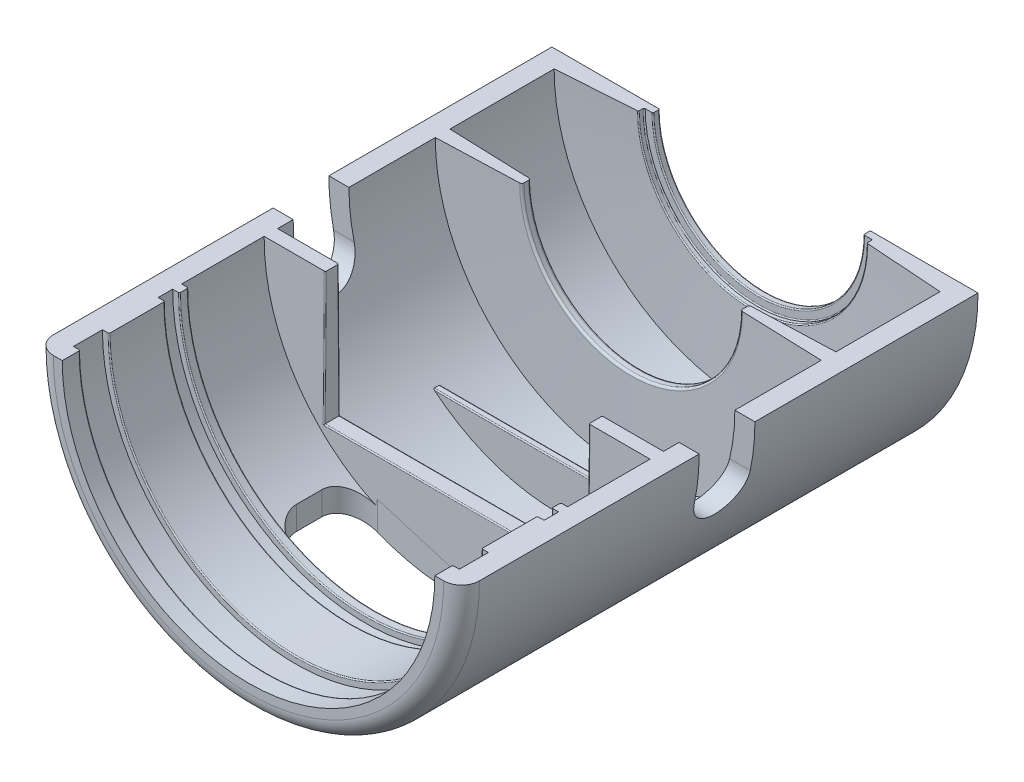
SolidWorks part; units mm, degrees
material "PC High Viscosity"
ref_plane "Front Plane" through (0, 0, 0) normal (0, 0, 1) x (1, 0, 0)
ref_plane "Top Plane" through (0, 0, 0) normal (0, 1, 0) x (1, 0, 0)
ref_plane "Right Plane" through (0, 0, 0) normal (1, 0, 0) x (0, 0, -1)
sketch "Sketch2" plane through (0, 0, 0) normal (0, 0, 1) x (1, 0, 0)
  line L1 (-15, 15) -> (15, 15)
  line L2 (-15, 15) -> (-15, -15)
  line L3 (-15, -15) -> (15, -15)
  line L4 (15, 15) -> (15, -15)
  line L5 (-15, 15) -> (15, -15) construction
  line L6 (-15, -15) -> (15, 15) construction
  circle A0 centre (0, 0) radius 21.971
  circle A1 centre (0, 0) radius 24.257
  point P0 (0, 0)
  dimension "D2" = 2.286
  dimension "D3" = 43.942
  dimension "D1" = 30
sketch "Sketch3" plane through (0, 0, 0) normal (0, 0, 1) x (1, 0, 0)
  line L0 (-24.257, 0) -> (-21.971, 0)
  line L1 (21.971, 0) -> (24.257, 0)
  circle A0 centre (0, 0) radius 24.257 construction
  circle A1 centre (0, 0) radius 21.971 construction
  arc A2 (-21.971, 0) -> (21.971, 0) centre (0, 0) ccw
  arc A3 (-24.257, 0) -> (24.257, 0) centre (0, 0) ccw
extrude "Boss-Extrude1" add sketch "Sketch3" along normal blind 38.1
ref_axis "Axis1" through (0, 0, 38.1) along (0, 0, -1)
ref_plane "Plane1" through (0, 0, 0) normal (0, -1, 0) x (-1, 0, 0)
sketch "Sketch8" plane through (0, 0, 0) normal (0, -1, 0) x (-1, 0, 0)
  line L0 (21.971, 0) -> (21.971, -2.032)
  line L1 (21.971, -38.1) -> (21.971, 0) construction
  line L2 (21.971, -2.032) -> (13.1229, -1.4133)
  line L3 (13.0048, -1.2866) -> (13.0048, -0.889)
  line L4 (12.8778, -0.762) -> (12.1158, -0.762)
  line L5 (11.9888, -0.635) -> (11.9888, -0.127)
  line L6 (21.971, 0) -> (-21.971, 0) construction
  line L7 (12.1158, 0) -> (21.971, 0)
  line L8 (0, -38.1) -> (0, 0) construction
  arc A0 (11.9888, -0.127) -> (12.1158, 0) centre (12.1158, -0.127) cw
  arc A1 (12.1158, -0.762) -> (11.9888, -0.635) centre (12.1158, -0.635) cw
  arc A2 (13.0048, -0.889) -> (12.8778, -0.762) centre (12.8778, -0.889) ccw
  arc A3 (13.1229, -1.4133) -> (13.0048, -1.2866) centre (13.1318, -1.2866) cw
  point P15 (11.9888, 0)
  point P18 (11.9888, -0.762)
  point P21 (13.0048, -0.762)
  dimension "D6" = 0.127
  dimension "D1" = 2.032
  dimension "D2" = 0.762
  dimension "D3" = 1.016
  dimension "D4" = 11.9888
  dimension "D5" = 86
revolve "Revolve1" add sketch "Sketch8" angle 180 about axis through (0, 0, 38.1) along (0, 0, -1)
sketch "Sketch9" plane through (0, 0, 0) normal (0, -1, 0) x (-1, 0, 0)
  line L0 (21.971, -14.732) -> (12.446, -14.732) construction
  line L1 (21.971, -38.1) -> (21.971, -2.032) construction
  line L2 (12.446, -14.9862) -> (12.446, -14.4778)
  line L3 (12.6911, -14.224) -> (21.971, -13.8999)
  line L4 (12.6911, -15.24) -> (21.971, -15.5641)
  line L5 (21.971, -15.5641) -> (21.971, -13.8999)
  line L6 (12.1158, -0.762) -> (12.8778, -0.762) construction
  line L7 (0, -38.1) -> (0, 0) construction
  arc A0 (12.446, -14.4778) -> (12.6911, -14.224) centre (12.7, -14.4778) cw
  arc A1 (12.446, -14.9862) -> (12.6911, -15.24) centre (12.7, -14.9862) ccw
  dimension "D1" = 0.254
  dimension "D2" = 1.016
  dimension "D3" = 4
  dimension "D4" = 13.97
  dimension "D5" = 12.446
revolve "Revolve2" add sketch "Sketch9" angle 180 about axis through (0, 0, 38.1) along (0, 0, -1)
ref_plane "Plane2" through (0, -17.5768, 0) normal (0, -1, 0) x (-1, 0, 0)
sketch "Sketch11" plane through (0, -17.5768, 0) normal (0, -1, 0) x (-1, 0, 0)
  line L0 (0, -36.9414) -> (0, -6.0033) construction
  line L1 (0, -38.1) -> (0, 0) construction
  line L2 (-13.97, -22.098) -> (13.97, -22.098)
  line L3 (13.97, -22.098) -> (13.97, -23.622)
  line L4 (13.97, -23.622) -> (-13.97, -23.622)
  line L5 (-13.97, -22.098) -> (-13.97, -23.622)
  line L6 (13.97, -22.86) -> (-13.97, -22.86) construction
  line L9 (-24.257, 0) -> (-12.1158, 0) construction
  point P10 (0, -23.622)
  point P11 (0, -22.098)
  dimension "D1" = 1.524
  dimension "D2" = 27.94
  dimension "D3" = 22.86
extrude "Boss-Extrude6" add sketch "Sketch11" along normal up to body
ref_plane "Plane3" through (0, -16.8148, 0) normal (0, 1, 0) x (1, 0, 0)
sketch "Sketch12" plane through (0, -16.8148, 0) normal (0, 1, 0) x (1, 0, 0)
  line L0 (14.605, -23.622) -> (-14.605, -23.622)
  line L2 (-13.1826, -23.622) -> (13.1826, -23.622) construction
  line L3 (-14.605, -23.622) -> (-14.605, -22.86)
  line L4 (-14.605, -22.86) -> (14.605, -22.86)
  line L5 (0, -38.1) -> (0, 0) construction
  line L6 (0, -22.86) -> (0, -27.3543) construction
  line L7 (14.605, -23.622) -> (14.605, -22.86)
  point P12 (0, -23.622)
  dimension "D1" = 0.762
  dimension "D2" = 29.21
extrude "Boss-Extrude7" add sketch "Sketch12" against normal up to surface (0.762 mm away) up to face at (0, -17.5768, 22.86)
ref_plane "Plane4" through (0, 0, 0) normal (1, 0, 0) x (0, 0, -1)
sketch "Sketch13" plane through (0, 0, 0) normal (1, 0, 0) x (0, 0, -1)
  line L0 (-22.86, -17.5768) -> (-22.86, 0) construction
  line L2 (-38.1, 0) -> (0, 0) construction
  line L3 (-25.4, 0) -> (-25.4, -5.08)
  line L4 (-31.75, 0) -> (-31.75, -5.08)
  line L5 (-31.75, -5.08) -> (-25.4, -5.08) construction
  line L6 (-38.1, 0) -> (0, 0) construction
  arc A0 (-31.75, -5.08) -> (-25.4, -5.08) centre (-28.575, -5.08) ccw
  point P12 (-28.575, -8.255)
  dimension "D2" = 3.175
  dimension "D1" = 6.35
  dimension "D3" = 2.54
  dimension "D4" = 8.255
extrude "Cut-Extrude1" cut sketch "Sketch13" against normal through all and the other way through all
sketch "Sketch15" plane through (0, 0, 0) normal (0, -1, 0) x (-1, 0, 0)
  line L0 (21.971, -44.45) -> (21.209, -44.45)
  line L1 (21.971, -38.1) -> (21.971, -31.75) construction
  line L2 (21.209, -44.45) -> (21.209, -45.466)
  line L3 (21.209, -45.466) -> (21.971, -45.466)
  line L4 (21.971, -45.466) -> (21.971, -47.117)
  line L5 (21.971, -47.117) -> (21.209, -47.117)
  line L6 (21.209, -47.117) -> (21.209, -53.467)
  line L7 (21.209, -53.467) -> (21.971, -53.467)
  line L8 (21.971, -53.467) -> (21.971, -56.769)
  line L9 (21.971, -56.769) -> (21.209, -56.769)
  line L10 (21.209, -56.769) -> (21.209, -58.801)
  line L11 (21.209, -58.801) -> (24.257, -58.801)
  line L12 (24.257, -58.801) -> (24.257, -52.4274)
  line L13 (24.257, -38.1) -> (24.257, -31.75) construction
  line L14 (24.257, -52.4274) -> (24.257, -44.45)
  line L15 (24.257, -44.45) -> (21.971, -44.45)
  line L16 (14.1417, -22.86) -> (13.1826, -22.86) construction
  line L17 (0, -25.7525) -> (0, -35.3346) construction
  line L18 (0, -38.1) -> (0, 0) construction
  dimension "D1" = 22.606
  dimension "D2" = 21.971
  dimension "D3" = 1.651
  dimension "D4" = 3.302
  dimension "D5" = 6.35
  dimension "D6" = 2.032
  dimension "D7" = 21.209
  dimension "D8" = 0.762
  dimension "D9" = 1.016
revolve "Revolve3" add sketch "Sketch15" angle 180 about axis through (0, 0, 38.1) along (0, 0, -1)
sketch "Sketch16" plane through (0, 0, 38.1) normal (0, 0, 1) x (1, 0, 0)
  line L2 (24.257, 0) -> (21.971, 0)
  line L3 (-21.971, 0) -> (-24.257, 0)
  line L4 (24.257, 0) -> (21.971, 0)
  line L5 (-21.971, 0) -> (-24.257, 0)
  arc A2 (-24.257, 0) -> (24.257, 0) centre (0, 0) ccw
  arc A3 (-21.971, 0) -> (21.971, 0) centre (0, 0) ccw
  arc A4 (-24.257, 0) -> (24.257, 0) centre (0, 0) ccw
  arc A5 (-21.971, 0) -> (21.971, 0) centre (0, 0) ccw
  dimension "D1" = 0
extrude "Boss-Extrude9" add sketch "Sketch16" along normal up to surface (6.35 mm away)
sketch "Sketch18" plane through (0, 0, 0) normal (0, -1, 0) x (-1, 0, 0)
  line L0 (-21.971, -44.45) -> (-21.971, -31.75) construction
  line L1 (-21.971, -33.528) -> (21.971, -33.528)
  line L2 (-21.971, -33.528) -> (-21.971, -35.052)
  line L3 (-21.971, -35.052) -> (21.971, -35.052)
  line L4 (21.971, -33.528) -> (21.971, -35.052)
  line L5 (21.971, -44.45) -> (21.971, -31.75) construction
  line L6 (-14.1417, -22.86) -> (14.1417, -22.86) construction
  dimension "D1" = 1.524
  dimension "D2" = 12.192
extrude "Boss-Extrude10" add sketch "Sketch18" along normal up to body draft 0.5 draft outward yes
ref_plane "Plane5" through (0, 0, 33.528) normal (0, 0, 1) x (1, 0, 0)
sketch "Sketch21" plane through (0, 0, 33.528) normal (0, 0, 1) x (1, 0, 0)
  line L1 (-15, 15) -> (15, 15)
  line L2 (-15, 15) -> (-15, -15)
  line L3 (-15, -15) -> (15, -15)
  line L4 (15, 15) -> (15, -15)
  line L5 (-15, 15) -> (15, -15) construction
  line L6 (-15, -15) -> (15, 15) construction
  point P0 (0, 0)
  dimension "D1" = 30
extrude "Cut-Extrude2" cut sketch "Sketch21" against normal up to next and the other way up to next
fillet "Fillet3" radius 0.127 14 edges at (0, -17.5768, 22.098) (0, -16.8148, 22.86) (0, -16.8148, 23.622) (0, -21.209, 56.769) (0, -21.209, 53.467) (0, -21.209, 47.117) (0, -21.209, 45.466) (0, -21.209, 44.45) (-15, -7.5, 35.1175) (-15, -7.5, 33.4625) (0, -15, 35.1829) (0, -15, 33.3971) (15, -7.5, 33.4625) (15, -7.5, 35.1175)
fillet "Fillet4" radius 2.032 1 edges at (0, -24.257, 58.801)
sketch "Sketch22" plane through (0, 0, 0) normal (0, -1, 0) x (-1, 0, 0)
  line L0 (0, -4.4618) -> (0, -49.8528) construction
  line L1 (0, -38.1) -> (0, 0) construction
  line L2 (8.89, -44.45) -> (-8.89, -44.45)
  line L3 (21.971, -44.45) -> (-21.971, -44.45) construction
  line L4 (21.336, -44.45) -> (-21.336, -44.45) construction
  line L6 (-12.065, -41.275) -> (-12.065, -38.3955)
  line L7 (-8.8817, -35.2206) -> (0, -35.2437)
  line L8 (8.8817, -35.2206) -> (0, -35.2437)
  line L9 (12.065, -41.275) -> (12.065, -38.3955)
  arc A0 (-12.065, -38.3955) -> (-8.8817, -35.2206) centre (-8.89, -38.3955) cw
  arc A1 (-8.89, -44.45) -> (-12.065, -41.275) centre (-8.89, -41.275) cw
  arc A2 (8.89, -44.45) -> (12.065, -41.275) centre (8.89, -41.275) ccw
  arc A3 (12.065, -38.3955) -> (8.8817, -35.2206) centre (8.89, -38.3955) ccw
  spline S1 degree 3 poles (-21.971, -35.052) (-21.971, -35.4355) (21.971, -35.4355) (21.971, -35.052) knots 0 0 0 0 1 1 1 1 weights 1 0.333333 0.333333 1 construction
  point P5 (12.065, -44.45)
  point P17 (-12.065, -35.2122)
  point P20 (-12.065, -44.45)
  point P27 (0, -44.45)
  point P28 (12.065, -35.2122)
  dimension "D1" = 3.175
  dimension "D3" = 3.175
  dimension "D2" = 3.175
  dimension "D4" = 17.78
  dimension "D5" = 9.2294
extrude "Cut-Extrude4" cut sketch "Sketch22" along normal through all
